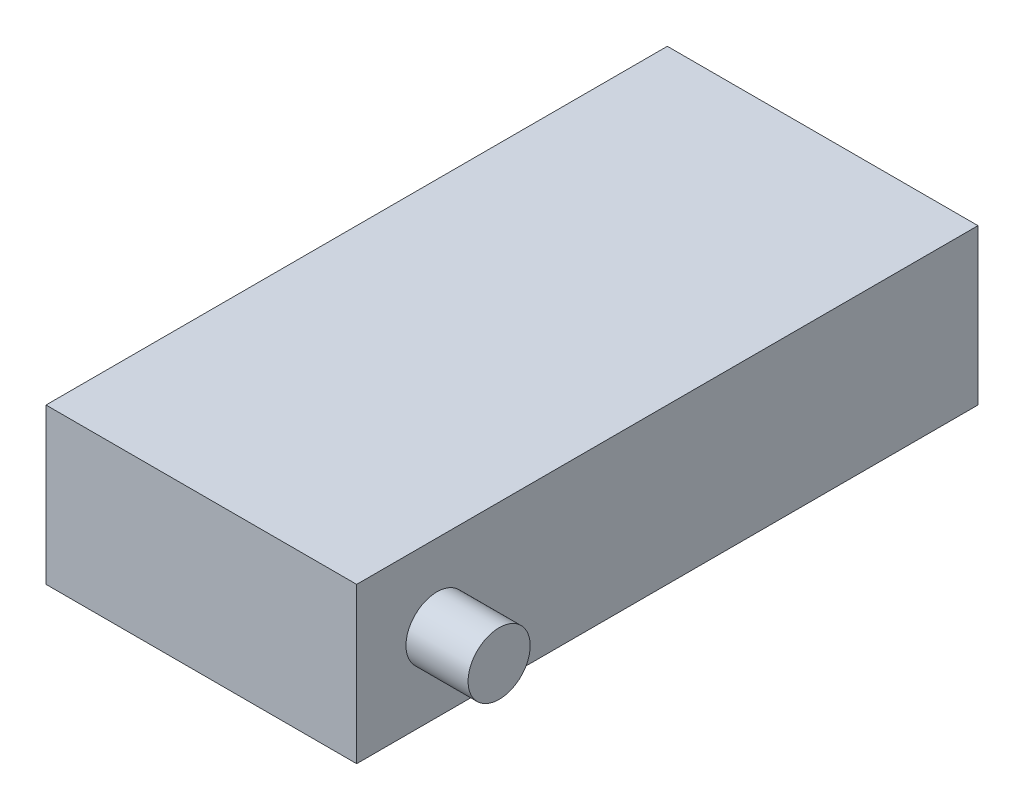
SolidWorks part; units mm, degrees
ref_plane "Front Plane" through (0, 0, 0) normal (0, 0, 1) x (1, 0, 0)
ref_plane "Top Plane" through (0, 0, 0) normal (0, 1, 0) x (1, 0, 0)
ref_plane "Right Plane" through (0, 0, 0) normal (1, 0, 0) x (0, 0, -1)
sketch "Sketch1" plane through (0, 0, 0) normal (1, 0, 0) x (0, 0, -1)
  line L1 (-13.6174, 8.4464) -> (26.3826, 8.4464)
  line L2 (-13.6174, 8.4464) -> (-13.6174, -1.5536)
  line L3 (-13.6174, -1.5536) -> (26.3826, -1.5536)
  line L4 (26.3826, 8.4464) -> (26.3826, -1.5536)
  dimension "D1" = 40
  dimension "D2" = 10
extrude "Boss-Extrude1" add sketch "Sketch1" along normal blind 20
sketch "Sketch2" plane through (20, 0, 0) normal (1, 0, 0) x (0, 0, -1)
  circle A0 centre (-8.4451, 3.4464) radius 2
extrude "Boss-Extrude2" add sketch "Sketch2" along normal blind 4
